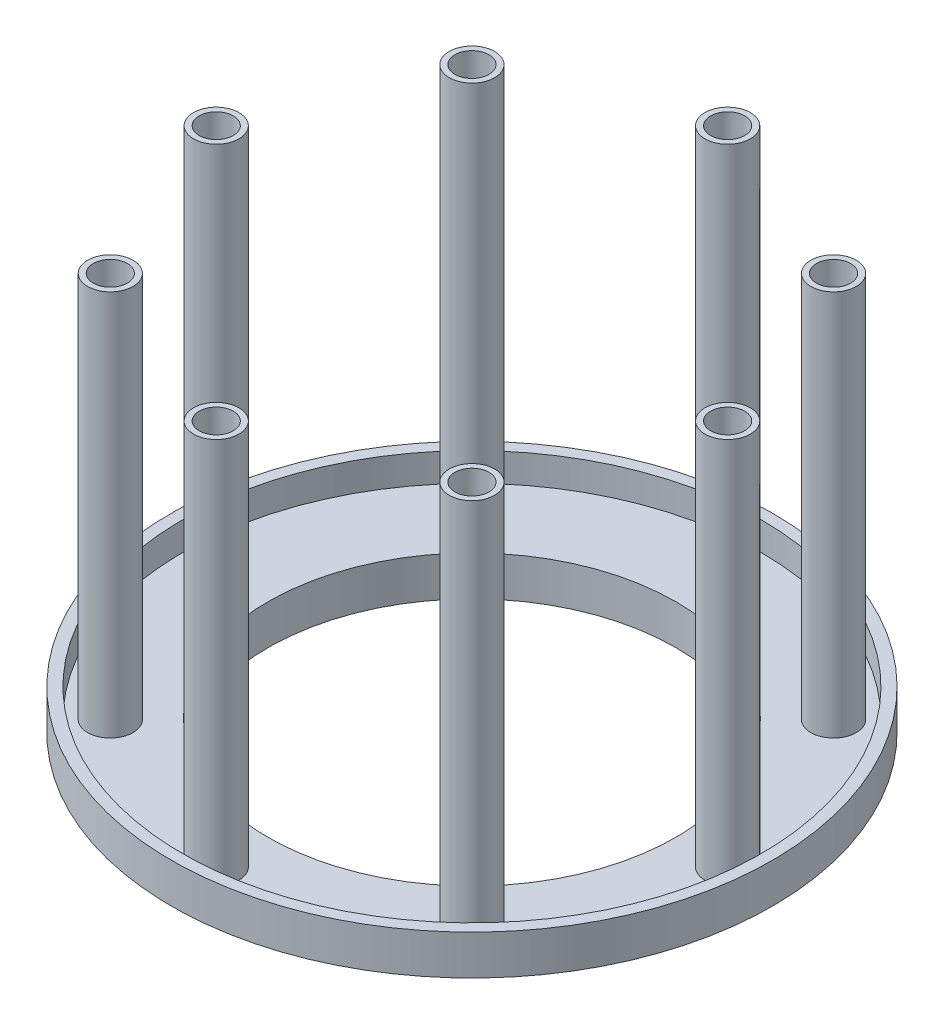
SolidWorks part; units mm, degrees
ref_plane "Ön Düzlem" through (0, 0, 0) normal (0, 0, 1) x (1, 0, 0)
ref_plane "Üst Düzlem" through (0, 0, 0) normal (0, 1, 0) x (1, 0, 0)
ref_plane "Sağ Düzlem" through (0, 0, 0) normal (1, 0, 0) x (0, 0, -1)
sketch "Çizim1" plane through (0, 0, 0) normal (0, 0, 1) x (1, 0, 0)
  line L0 (0, 0) -> (0, 14.2201) construction
  line L1 (-52.9, 7) -> (-52.9, 0)
  line L2 (-52.9, 0) -> (-37.9, 0)
  line L3 (-37.9, 0) -> (-37.9, -5)
  line L4 (-37.9, -5) -> (-35.9, -5)
  line L5 (-35.9, -5) -> (-35.9, 2)
  line L6 (-35.9, 2) -> (-50.9, 2)
  line L7 (-50.9, 2) -> (-50.9, 7)
  line L8 (-50.9, 7) -> (-52.9, 7)
  dimension "D1" = 7
  dimension "D2" = 7
  dimension "D3" = 2
  dimension "D4" = 2
  dimension "D5" = 2
  dimension "D6" = 15
  dimension "D7" = 35.9
revolve "Döndür1" add sketch "Çizim1" angle 360 about L0
sketch "Çizim2" plane through (0, 0, 0) normal (0, -1, 0) x (1, 0, 0)
  circle A0 centre (0, 45) radius 4
  dimension "D1" = 8
  dimension "D2" = 45
extrude "Kes-Ekstrüzyon1" cut sketch "Çizim2" against normal blind 10
chamfer "Pah1" distance 0.5 angle 45 1 edges at (0, 0, 41)
pattern_circular "Dairesel Kaplama8" count 8 over 360 about axis through (0, 0, 0) along (0, 1, 0) of "Kes-Ekstrüzyon1", "Pah1"
sketch "Çizim4" plane through (0, 0, 0) normal (0, -1, 0) x (1, 0, 0)
  circle A0 centre (0, 45) radius 3
  circle A1 centre (0, 45) radius 4
  circle A2 centre (31.8198, 31.8198) radius 3
  circle A3 centre (31.8198, 31.8198) radius 4
  circle A4 centre (45, 0) radius 3
  circle A5 centre (45, 0) radius 4
  circle A6 centre (31.8198, -31.8198) radius 3
  circle A7 centre (31.8198, -31.8198) radius 4
  circle A8 centre (0, -45) radius 3
  circle A9 centre (0, -45) radius 4
  circle A10 centre (-31.8198, -31.8198) radius 3
  circle A11 centre (-31.8198, -31.8198) radius 4
  circle A12 centre (-45, 0) radius 3
  circle A13 centre (-45, 0) radius 4
  circle A14 centre (-31.8198, 31.8198) radius 3
  circle A15 centre (-31.8198, 31.8198) radius 4
  point P35 (0, 0)
  dimension "D1" = 6
  dimension "D2" = 1
  dimension "D3" = 8
extrude "Yükseklik-Ekstrüzyon2" add sketch "Çizim4" against normal blind 70
